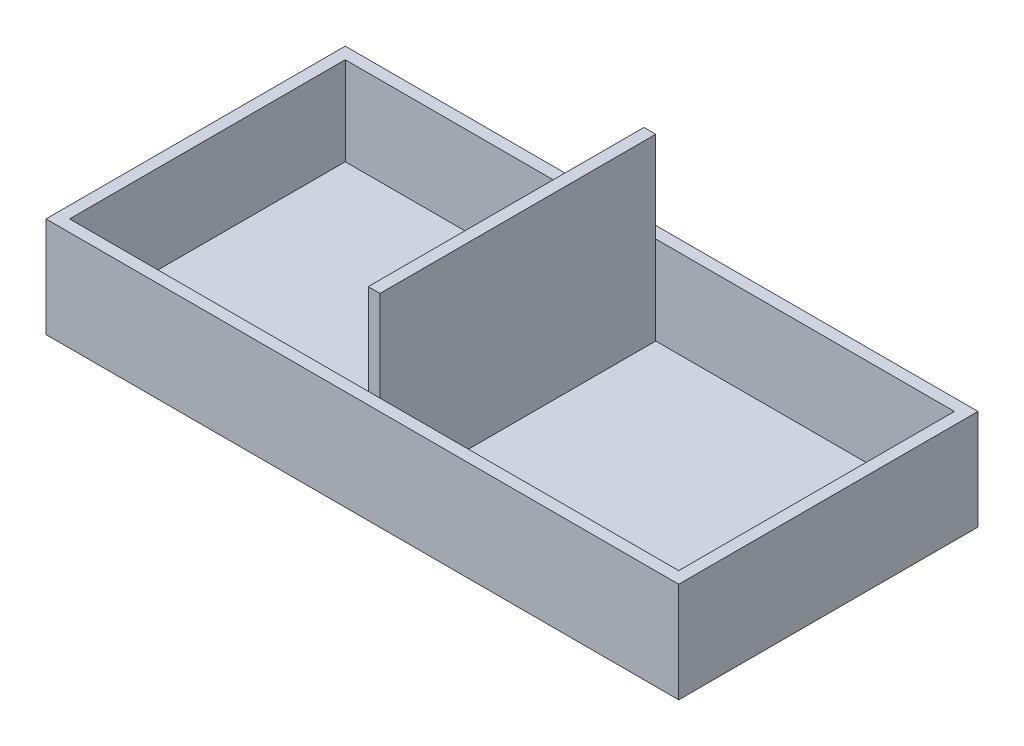
SolidWorks part; units mm, degrees
ref_plane "Front Plane" through (0, 0, 0) normal (0, 0, 1) x (1, 0, 0)
ref_plane "Top Plane" through (0, 0, 0) normal (0, 1, 0) x (1, 0, 0)
ref_plane "Right Plane" through (0, 0, 0) normal (1, 0, 0) x (0, 0, -1)
sketch "Sketch2" plane through (0, 0, 0) normal (0, 1, 0) x (1, 0, 0)
  line L1 (0, 0) -> (537, 0)
  line L2 (0, 0) -> (0, 254)
  line L3 (0, 254) -> (537, 254)
  line L4 (537, 0) -> (537, 254)
  dimension "D1" = 537
  dimension "D2" = 254
extrude "Boss-Extrude1" add sketch "Sketch2" along normal blind 85
sketch "Sketch3" plane through (0, 85, 0) normal (0, 1, 0) x (1, 0, 0)
  line L0 (537, 254) -> (0, 254) construction
  line L1 (10, 244) -> (527, 244)
  line L2 (10, 244) -> (10, 10)
  line L3 (10, 10) -> (527, 10)
  line L4 (527, 244) -> (527, 10)
  line L5 (0, 254) -> (0, 0) construction
  line L6 (0, 0) -> (537, 0) construction
  line L7 (537, 0) -> (537, 254) construction
  dimension "D1" = 10
  dimension "D2" = 10
  dimension "D3" = 10
  dimension "D4" = 10
extrude "Cut-Extrude1" cut sketch "Sketch3" against normal blind 75
sketch "Sketch4" plane through (0, 10, 0) normal (0, 1, 0) x (1, 0, 0)
  line L0 (268.5, 305.8432) -> (268.5, -37.1705) construction
  line L1 (263.5, 244) -> (273.5, 244)
  line L2 (263.5, 244) -> (263.5, 10)
  line L3 (263.5, 10) -> (273.5, 10)
  line L4 (273.5, 244) -> (273.5, 10)
  line L5 (10, 244) -> (10, 10) construction
  line L6 (527, 10) -> (527, 244) construction
  line L8 (527, 244) -> (10, 244) construction
  line L9 (10, 10) -> (527, 10) construction
  dimension "D1" = 10
extrude "Boss-Extrude2" add sketch "Sketch4" along normal blind 152
